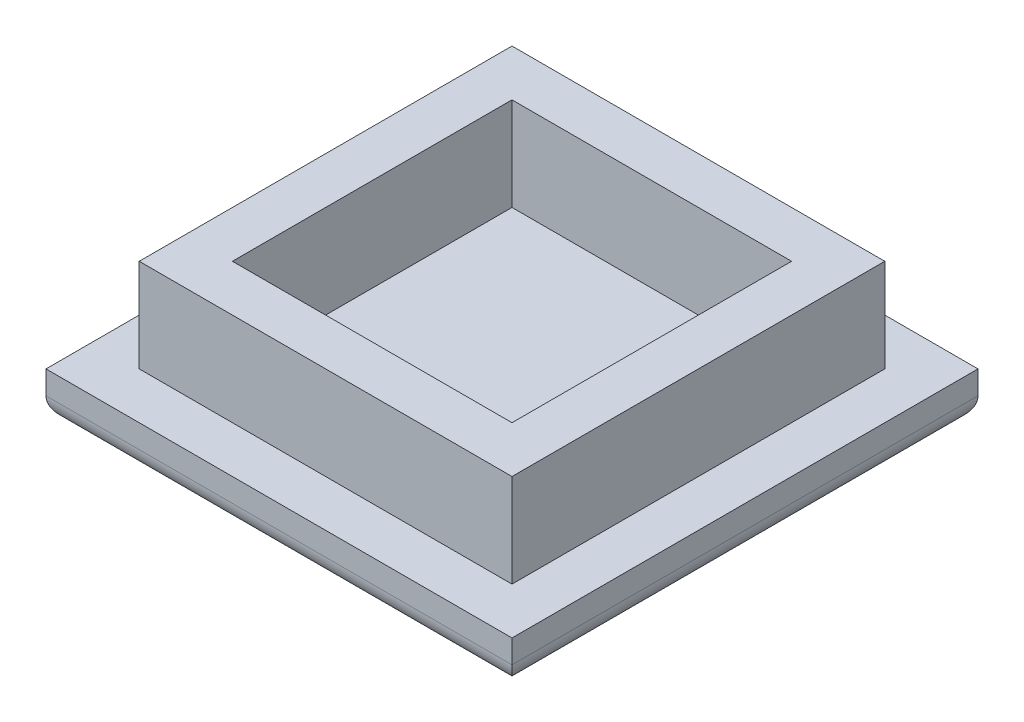
SolidWorks part; units mm, degrees
ref_plane "Front Plane" through (0, 0, 0) normal (0, 0, 1) x (1, 0, 0)
ref_plane "Top Plane" through (0, 0, 0) normal (0, 1, 0) x (1, 0, 0)
ref_plane "Right Plane" through (0, 0, 0) normal (1, 0, 0) x (0, 0, -1)
sketch "Sketch1" plane through (0, 0, 0) normal (0, 1, 0) x (1, 0, 0)
  line L1 (-10, -10) -> (10, -10)
  line L2 (-10, -10) -> (-10, 10)
  line L3 (-10, 10) -> (10, 10)
  line L4 (10, -10) -> (10, 10)
  line L5 (-10, -10) -> (10, 10) construction
  line L6 (-10, 10) -> (10, -10) construction
  point P0 (0, 0)
  dimension "D1" = 20
extrude "Boss-Extrude1" add sketch "Sketch1" along normal blind 2
sketch "Sketch2" plane through (0, 2, 0) normal (0, 1, 0) x (1, 0, 0)
  line L0 (-6, 6) -> (6, 6)
  line L1 (-8, -8) -> (8, -8)
  line L2 (-8, -8) -> (-8, 8)
  line L3 (-8, 8) -> (8, 8)
  line L4 (8, -8) -> (8, 8)
  line L5 (-8, -8) -> (8, 8) construction
  line L6 (-8, 8) -> (8, -8) construction
  line L7 (6, -6) -> (6, 6)
  line L8 (-6, -6) -> (6, -6)
  line L9 (-6, -6) -> (-6, 6)
  point P0 (0, 0)
  dimension "D1" = 16
  dimension "D2" = 2
extrude "Boss-Extrude2" add sketch "Sketch2" along normal blind 4
fillet "Fillet1" radius 1 4 edges at (0, 0, -10) (-10, 0, 0) (0, 0, 10) (10, 0, 0)
